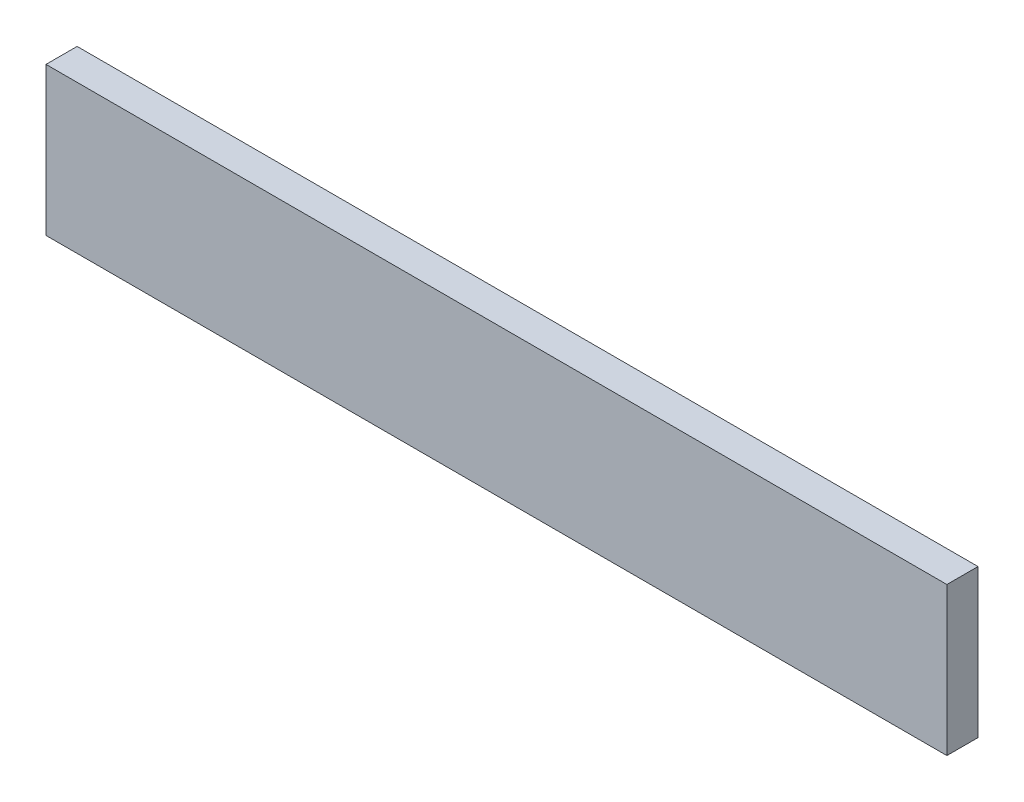
SolidWorks part; units mm, degrees
ref_plane "Front Plane" through (0, 0, 0) normal (0, 0, 1) x (1, 0, 0)
ref_plane "Top Plane" through (0, 0, 0) normal (0, 1, 0) x (1, 0, 0)
ref_plane "Right Plane" through (0, 0, 0) normal (1, 0, 0) x (0, 0, -1)
sketch "Sketch1" plane through (0, 0, 0) normal (0, 0, 1) x (1, 0, 0)
  line L1 (0, 0) -> (154.432, 0)
  line L2 (0, 0) -> (0, 25.4)
  line L3 (0, 25.4) -> (154.432, 25.4)
  line L4 (154.432, 0) -> (154.432, 25.4)
  dimension "D1" = 25.4
  dimension "D2" = 154.432
extrude "Boss-Extrude1" add sketch "Sketch1" along normal mid plane 5.334
equation "\"material\"= \"GMaterial@MotorizedPlatform.assembly\""
equation "\"D1@Boss-Extrude1\" = \"material\""
equation "\"D2@Sketch1\" = 6.5 - (\"material\" * 2)"
